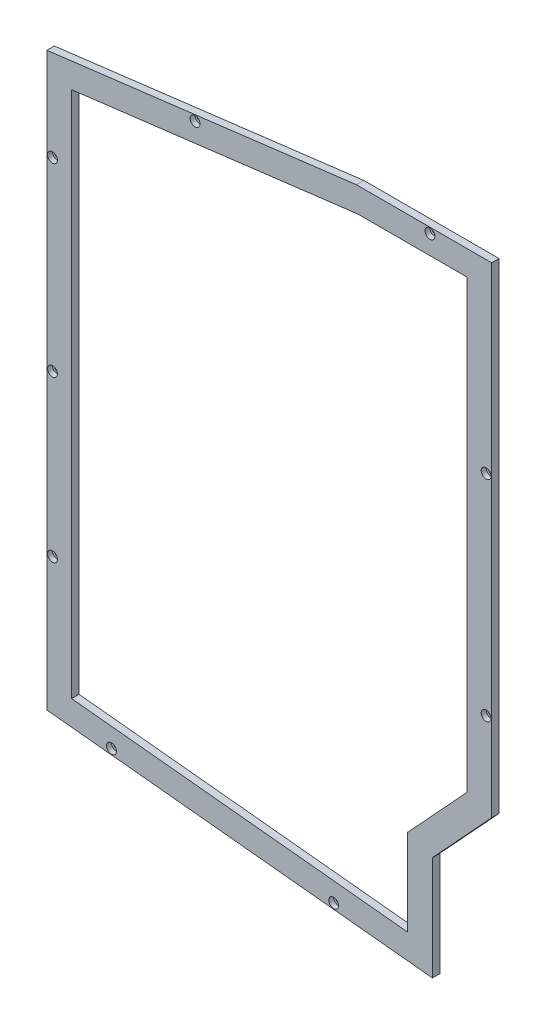
SolidWorks part; units mm, degrees
ref_plane "Plan de face" through (0, 0, 0) normal (0, 0, 1) x (1, 0, 0)
ref_plane "Plan de dessus" through (0, 0, 0) normal (0, 1, 0) x (1, 0, 0)
ref_plane "Plan de droite" through (0, 0, 0) normal (1, 0, 0) x (0, 0, -1)
sketch "Esquisse1" plane through (0, 0, 0) normal (0, 0, 1) x (1, 0, 0)
  line L0 (-377.3, 239.0359) -> (-377.3, 20.8708)
  line L1 (-377.3, 20.8708) -> (-65, -10.9641)
  line L2 (-65, -10.9641) -> (-65, 73.4811)
  line L3 (-65, 73.4811) -> (-17, 125.4811)
  line L4 (-17, 125.4811) -> (-17, 225.4811)
  line L5 (-357.3, 225.4811) -> (-357.3, 38.9357)
  line L6 (-357.3, 38.9357) -> (-85, 11.1783)
  line L7 (-75, 0.1071) -> (-75, 77.391)
  line L8 (-75, 77.391) -> (-27, 129.391)
  line L9 (-27, 129.391) -> (-27, 504.8433)
  line L10 (-27, 504.8433) -> (-125.9383, 504.8433)
  line L11 (-125.9383, 504.8433) -> (-367.3, 474.9594)
  line L12 (-367.3, 474.9594) -> (-367.3, 29.9032)
  line L13 (-367.3, 29.9032) -> (-75, 0.1071)
  line L14 (-75, 0.1071) -> (-75, 77.391) construction
  line L15 (-75, 77.391) -> (-27, 129.391) construction
  line L16 (-27, 129.391) -> (-27, 504.8433) construction
  line L17 (-27, 504.8433) -> (-125.9383, 504.8433) construction
  line L18 (-125.9383, 504.8433) -> (-367.3, 474.9594) construction
  line L19 (-367.3, 474.9594) -> (-367.3, 29.9032) construction
  line L20 (-367.3, 29.9032) -> (-75, 0.1071) construction
  line L21 (-85, 11.1783) -> (-85, 81.3008)
  line L22 (-85, 81.3008) -> (-37, 133.3008)
  line L23 (-37, 133.3008) -> (-37, 239.0359)
  line L24 (-17, 225.4811) -> (-37, 239.0359)
  line L25 (-357.3, 225.4811) -> (-377.3, 239.0359)
  line L27 (-37, 133.3008) -> (-37, 504.8433) construction
  line L28 (-17, 125.4811) -> (-17, 504.8433) construction
  line L29 (-357.3, 474.9594) -> (-357.3, 38.9357) construction
  line L30 (-377.3, 474.9594) -> (-377.3, 20.8708) construction
  dimension "D4" = 250
  dimension "D5" = 100
  dimension "D1" = 0
  dimension "D2" = 10
  dimension "D3" = 10
extrude "Boss.-Extru.1" add sketch "Esquisse1" along normal blind 6
sketch "Esquisse3" plane through (0, 0, 0) normal (0, 0, 1) x (1, 0, 0)
  line L0 (-17, 225.4811) -> (-17, 514.8433)
  line L1 (-17, 514.8433) -> (-126.555, 514.8433)
  line L2 (-126.555, 514.8433) -> (-377.3, 483.7977)
  line L3 (-377.3, 483.7977) -> (-377.3, 239.0359)
  line L4 (-37, 239.0359) -> (-37, 494.8433)
  line L5 (-37, 494.8433) -> (-125.3216, 494.8433)
  line L6 (-125.3216, 494.8433) -> (-357.3, 466.1212)
  line L7 (-75, 0.1071) -> (-75, 77.391)
  line L8 (-75, 77.391) -> (-27, 129.391)
  line L9 (-27, 129.391) -> (-27, 504.8433)
  line L10 (-27, 504.8433) -> (-125.9383, 504.8433)
  line L11 (-125.9383, 504.8433) -> (-367.3, 474.9594)
  line L12 (-367.3, 474.9594) -> (-367.3, 29.9032)
  line L13 (-367.3, 29.9032) -> (-75, 0.1071)
  line L14 (-75, 0.1071) -> (-75, 77.391) construction
  line L15 (-75, 77.391) -> (-27, 129.391) construction
  line L16 (-27, 129.391) -> (-27, 504.8433) construction
  line L17 (-27, 504.8433) -> (-125.9383, 504.8433) construction
  line L18 (-125.9383, 504.8433) -> (-367.3, 474.9594) construction
  line L19 (-367.3, 474.9594) -> (-367.3, 29.9032) construction
  line L20 (-367.3, 29.9032) -> (-75, 0.1071) construction
  line L21 (-357.3, 466.1212) -> (-357.3, 225.4811)
  line L23 (-37, 239.0359) -> (-17, 225.4811)
  line L24 (-17, 225.4811) -> (-37, 239.0359) construction
  line L25 (-357.3, 225.4811) -> (-377.3, 239.0359)
  line L26 (-357.3, 225.4811) -> (-377.3, 239.0359) construction
  line L28 (-17, 129.391) -> (-17, 514.8433) construction
  line L29 (-37, 129.391) -> (-37, 494.8433) construction
  line L30 (-357.3, 466.1212) -> (-357.3, 29.9032) construction
  line L31 (-377.3, 483.7977) -> (-377.3, 29.9032) construction
  dimension "D1" = 0
  dimension "D2" = 10
  dimension "D3" = 10
extrude "Boss.-Extru.2" add sketch "Esquisse3" along normal blind 6
hole_wizard "Chambrage pour vis à tête cylindrique à 6 pans creux (ou vis CHC) M41" positions "Esquisse7" profile "Esquisse8" counterbore size "M4" standard "Ansi Metric"
sketch "Esquisse7" plane through (0, 0, 6) normal (0, 0, 1) x (1, 0, 0)
  line L0 (-74, -1) -> (-65, -1.9174) construction
  line L1 (-65, -10.9641) -> (-65, 73.4811) construction
  line L3 (-74, -1) -> (-368.3, 29) construction
  line L4 (-69.5, -1.4587) -> (-69.5, -10.5054) construction
  line L5 (-377.3, 20.8708) -> (-65, -10.9641) construction
  line L7 (-69.5, -5.982) -> (-377.3, 25.3941) construction
  line L9 (-377.3, 483.7977) -> (-377.3, 20.8708) construction
  line L29 (-21.5, 125.4811) -> (-21.5, 510.3433)
  line L30 (-21.5, 510.3433) -> (-126.2775, 510.3433)
  line L31 (-126.2775, 510.3433) -> (-372.8, 479.8205)
  line L32 (-372.8, 479.8205) -> (-372.8, 20.8708)
  line L33 (-21.5, 125.4811) -> (-21.5, 510.3433) construction
  line L34 (-21.5, 510.3433) -> (-126.2775, 510.3433) construction
  line L35 (-126.2775, 510.3433) -> (-372.8, 479.8205) construction
  line L36 (-372.8, 479.8205) -> (-372.8, 20.8708) construction
  line L37 (-17, 125.4811) -> (-17, 514.8433) construction
  line L38 (-17, 514.8433) -> (-126.555, 514.8433) construction
  point P0 (-145, 1.7142)
  point P4 (-325, 20.0628)
  point P6 (-372.8, 130.8708)
  point P8 (-372.8, 260.8708)
  point P10 (-372.8, 410.8708)
  point P12 (-257.3, 494.1209)
  point P14 (-67, 510.3433)
  point P16 (-21.5, 194.8433)
  point P18 (-21.5, 364.8433)
  dimension "D1" = 80
  dimension "D2" = 180
  dimension "D3" = 4.5
  dimension "D4" = 110
  dimension "D5" = 130
  dimension "D6" = 150
  dimension "D7" = 120
  dimension "D8" = 50
  dimension "D9" = 150
  dimension "D10" = 170
sketch "Esquisse8" plane through (-145, 1.7142, 6) normal (1, 0, 0) x (0, -1, 0)
  line L0 (0, 0) -> (0, 15.2919)
  line L1 (0, 15.2919) -> (2.15, 14)
  line L2 (2.15, 14) -> (2.15, 4)
  line L3 (2.15, 4) -> (4, 4)
  line L4 (4, 4) -> (4, 0)
  line L5 (4, 0) -> (0, 0)
  line L10 (0, 15.2919) -> (-2.15, 14) construction
  line L11 (0, -6.35) -> (0, 107.95) construction
  dimension "Diamètre du perçage" = 4.3
  dimension "Profondeur du perçage" = 14
  dimension "Diamètre du chambrage" = 8
  dimension "Profondeur du chambrage" = 4
  dimension "Angle de pointe" = 118
